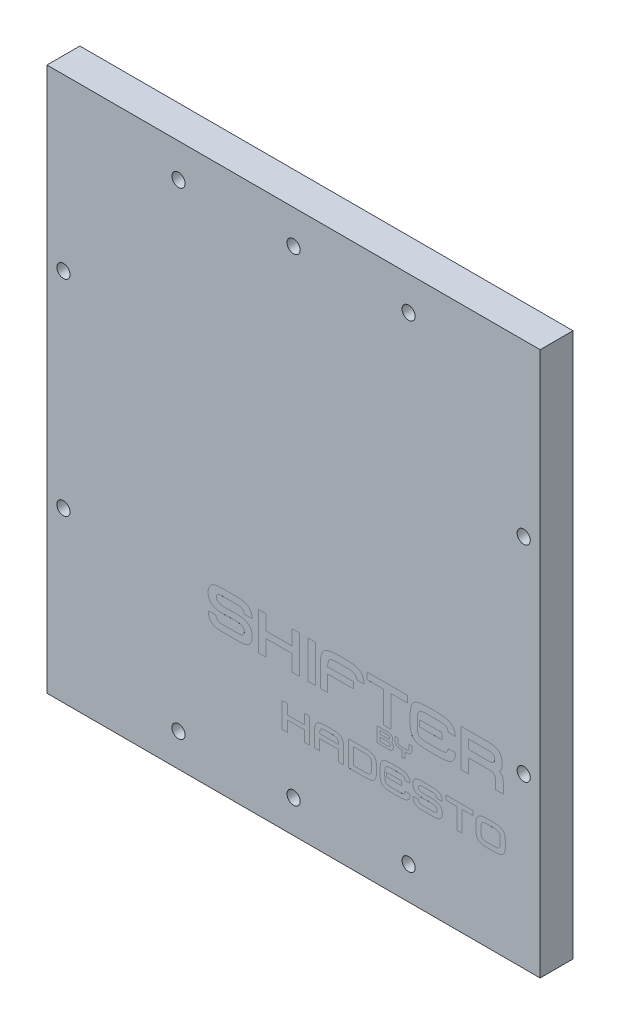
SolidWorks part; units mm, degrees
material "Oak"
ref_plane "Front Plane" through (0, 0, 0) normal (0, 0, 1) x (1, 0, 0)
ref_plane "Top Plane" through (0, 0, 0) normal (0, 1, 0) x (1, 0, 0)
ref_plane "Right Plane" through (0, 0, 0) normal (1, 0, 0) x (0, 0, -1)
sketch "Szkic1" plane through (0, 0, 0) normal (0, 1, 0) x (1, 0, 0)
  line L1 (-75, -5) -> (75, -5)
  line L2 (-75, -5) -> (-75, 5)
  line L3 (-75, 5) -> (75, 5)
  line L4 (75, -5) -> (75, 5)
  line L5 (-75, -5) -> (75, 5) construction
  line L6 (-75, 5) -> (75, -5) construction
  point P0 (0, 0)
extrude "Dodanie-wyciągnięcie1" add sketch "Szkic1" along normal blind 165.5
sketch "Szkic2" plane through (0, 0, 5) normal (0, 0, 1) x (1, 0, 0)
  line L0 (-75, 165.5) -> (-75, 155.25) construction
  line L1 (-75, 165.5) -> (-75, 0) construction
  line L2 (-75, 155.25) -> (-35, 155.25) construction
  line L3 (-35, 155.25) -> (0, 155.25) construction
  line L4 (0, 155.25) -> (35, 155.25) construction
  line L5 (75, 0) -> (75, 10) construction
  line L6 (75, 165.5) -> (75, 0) construction
  line L7 (75, 10) -> (35, 10) construction
  line L8 (35, 10) -> (0, 10) construction
  line L9 (0, 10) -> (-35, 10) construction
  line L10 (-75, 155.25) -> (-75, 145) construction
  line L11 (-75, 145) -> (-70, 145) construction
  line L12 (-70, 145) -> (-70, 113.75) construction
  line L13 (-70, 113.75) -> (-70, 51.25) construction
  line L14 (75, 10) -> (75, 20) construction
  line L15 (75, 20) -> (70, 20) construction
  line L16 (70, 20) -> (70, 51.25) construction
  line L17 (70, 51.25) -> (70, 113.75) construction
  line L18 (-35, 165.5) -> (-35, 155.25) construction
  line L19 (-75, 165.5) -> (75, 165.5) construction
  circle A0 centre (-35, 155.25) radius 2
  circle A1 centre (0, 155.25) radius 2
  circle A2 centre (35, 155.25) radius 2
  circle A3 centre (-35, 10) radius 2
  circle A4 centre (0, 10) radius 2
  circle A5 centre (35, 10) radius 2
  circle A6 centre (-70, 113.75) radius 2
  circle A7 centre (-70, 51.25) radius 2
  circle A8 centre (70, 113.75) radius 2
  circle A9 centre (70, 51.25) radius 2
sketch "Szkic3" plane through (0, 0, 5) normal (0, 0, 1) x (1, 0, 0)
  line L0 (-16.5425, 42.8324) -> (-22.1233, 42.8324)
  line L1 (-25.9282, 46.2952) -> (-23.5548, 46.2952)
  line L2 (-21.7883, 44.8332) -> (-16.9713, 44.8332)
  line L3 (-22.1537, 54.2751) -> (-16.8447, 54.2751)
  line L4 (-12.6205, 50.8264) -> (-15.0712, 50.8264)
  line L5 (-17.0205, 52.2883) -> (-22.0272, 52.2883)
  line L6 (1.875, 42.8324) -> (-0.4656, 42.8324)
  line L7 (-0.4656, 42.8324) -> (-0.4656, 47.7431)
  line L8 (-0.4656, 47.7431) -> (-8.3283, 47.7431)
  line L9 (-8.3283, 47.7431) -> (-8.3283, 42.8324)
  line L10 (-8.3283, 42.8324) -> (-10.6689, 42.8324)
  line L11 (-10.6689, 42.8324) -> (-10.6689, 54.2751)
  line L12 (-10.6689, 54.2751) -> (-8.3283, 54.2751)
  line L13 (-8.3283, 54.2751) -> (-8.3283, 49.7275)
  line L14 (-8.3283, 49.7275) -> (-0.4656, 49.7275)
  line L15 (-0.4656, 49.7275) -> (-0.4656, 54.2751)
  line L16 (-0.4656, 54.2751) -> (1.875, 54.2751)
  line L17 (1.875, 54.2751) -> (1.875, 42.8324)
  line L18 (6.706, 42.8324) -> (4.3655, 42.8324)
  line L19 (4.3655, 42.8324) -> (4.3655, 54.2751)
  line L20 (4.3655, 54.2751) -> (6.706, 54.2751)
  line L21 (6.706, 54.2751) -> (6.706, 42.8324)
  line L22 (10.3539, 49.6807) -> (18.205, 49.6807)
  line L23 (18.205, 49.6807) -> (18.205, 47.7759)
  line L24 (18.205, 47.7759) -> (10.3539, 47.7759)
  line L25 (10.3539, 47.7759) -> (10.3539, 42.8324)
  line L26 (10.3539, 42.8324) -> (8.1235, 42.8324)
  line L27 (8.1235, 42.8324) -> (8.1399, 48.767)
  line L28 (13.7089, 54.3384) -> (15.7754, 54.3384)
  line L29 (21.5108, 50.653) -> (19.2944, 50.653)
  line L30 (15.6957, 52.3047) -> (13.8214, 52.3047)
  line L31 (34.6708, 52.2743) -> (29.6477, 52.2743)
  line L32 (29.6477, 52.2743) -> (29.6477, 42.8324)
  line L33 (29.6477, 42.8324) -> (27.3071, 42.8324)
  line L34 (27.3071, 42.8324) -> (27.3071, 52.2743)
  line L35 (27.3071, 52.2743) -> (22.3003, 52.2743)
  line L36 (22.3003, 52.2743) -> (22.3003, 54.2751)
  line L37 (22.3003, 54.2751) -> (34.6708, 54.2751)
  line L38 (34.6708, 54.2751) -> (34.6708, 52.2743)
  line L39 (43.4309, 42.8324) -> (40.9685, 42.8324)
  line L40 (40.999, 54.322) -> (43.4637, 54.322)
  line L41 (49.1991, 50.7467) -> (46.9523, 50.7467)
  line L42 (43.3841, 52.3211) -> (41.1115, 52.3211)
  line L43 (37.6252, 49.5284) -> (37.6276, 47.9235)
  line L44 (41.0623, 44.8004) -> (43.4005, 44.8004)
  line L45 (46.9687, 46.4217) -> (49.2296, 46.4217)
  line L46 (45.1764, 47.7759) -> (38.3328, 47.7993)
  line L47 (38.3328, 47.7993) -> (38.3328, 49.6971)
  line L48 (38.3328, 49.6971) -> (45.1764, 49.6971)
  line L49 (45.1764, 49.6971) -> (45.1764, 47.7759)
  line L50 (63.7883, 42.8324) -> (61.4642, 42.8324)
  line L51 (61.4642, 42.8324) -> (61.4642, 45.016)
  line L52 (59.4516, 47.1082) -> (53.2664, 47.0918)
  line L53 (53.2664, 47.0918) -> (53.2664, 42.8324)
  line L54 (53.2664, 42.8324) -> (50.9891, 42.8324)
  line L55 (50.9891, 42.8324) -> (50.9891, 54.2751)
  line L56 (50.9891, 54.2751) -> (59.2923, 54.2751)
  line L57 (63.7883, 45.7634) -> (63.7883, 42.8324)
  line L58 (59.468, 52.0681) -> (53.2664, 52.0681)
  line L59 (53.2664, 52.0681) -> (53.2664, 49.2988)
  line L60 (53.2664, 49.2988) -> (59.468, 49.2988)
  line L61 (4.9001, 26.251) -> (3.3398, 26.251)
  line L62 (3.3398, 26.251) -> (3.3398, 29.5248)
  line L63 (3.3398, 29.5248) -> (-1.9021, 29.5248)
  line L64 (-1.9021, 29.5248) -> (-1.9021, 26.251)
  line L65 (-1.9021, 26.251) -> (-3.4624, 26.251)
  line L66 (-3.4624, 26.251) -> (-3.4624, 33.8794)
  line L67 (-3.4624, 33.8794) -> (-1.9021, 33.8794)
  line L68 (-1.9021, 33.8794) -> (-1.9021, 30.8477)
  line L69 (-1.9021, 30.8477) -> (3.3398, 30.8477)
  line L70 (3.3398, 30.8477) -> (3.3398, 33.8794)
  line L71 (3.3398, 33.8794) -> (4.9001, 33.8794)
  line L72 (4.9001, 33.8794) -> (4.9001, 26.251)
  line L73 (7.9396, 30.8477) -> (13.6922, 30.8477)
  line L74 (11.5133, 32.5455) -> (9.9983, 32.5455)
  line L75 (13.7016, 29.5248) -> (7.9412, 29.5248)
  line L76 (7.9412, 29.5248) -> (7.9412, 26.251)
  line L77 (7.9412, 26.251) -> (6.3808, 26.251)
  line L78 (6.3808, 26.251) -> (6.3808, 30.7587)
  line L79 (9.828, 33.8794) -> (11.7039, 33.8794)
  line L80 (15.2635, 30.7587) -> (15.2635, 26.251)
  line L81 (15.2635, 26.251) -> (13.7016, 26.251)
  line L82 (13.7016, 26.251) -> (13.7016, 29.5248)
  line L83 (21.9892, 26.24) -> (16.6552, 26.24)
  line L84 (16.6552, 26.24) -> (16.6552, 33.8794)
  line L85 (16.6552, 33.8794) -> (21.8096, 33.8794)
  line L86 (23.7011, 29.6138) -> (23.7011, 30.5463)
  line L87 (21.7252, 32.5549) -> (18.2265, 32.5549)
  line L88 (18.2265, 32.5549) -> (18.2265, 27.5739)
  line L89 (18.2265, 27.5739) -> (21.8205, 27.5739)
  line L90 (31.6044, 26.251) -> (29.9629, 26.251)
  line L91 (29.9832, 33.9107) -> (31.6263, 33.9107)
  line L92 (35.4499, 31.5272) -> (33.952, 31.5272)
  line L93 (31.5732, 32.5768) -> (30.0581, 32.5768)
  line L94 (27.734, 30.715) -> (27.7355, 29.645)
  line L95 (30.0253, 27.563) -> (31.5841, 27.563)
  line L96 (33.963, 28.6438) -> (35.4702, 28.6438)
  line L97 (32.7681, 29.5466) -> (28.2057, 29.5623)
  line L98 (28.2057, 29.5623) -> (28.2057, 30.8337)
  line L99 (28.2057, 30.8337) -> (32.7681, 30.8274)
  line L100 (32.7681, 30.8274) -> (32.7681, 29.5466)
  line L101 (42.6036, 26.251) -> (38.883, 26.251)
  line L102 (36.3465, 28.5595) -> (37.9287, 28.5595)
  line L103 (39.1064, 27.5848) -> (42.3177, 27.5848)
  line L104 (38.8627, 33.8794) -> (42.4021, 33.8794)
  line L105 (45.2182, 31.5803) -> (43.5845, 31.5803)
  line L106 (42.2849, 32.5549) -> (38.9471, 32.5549)
  line L107 (54.5539, 32.5455) -> (51.2051, 32.5455)
  line L108 (51.2051, 32.5455) -> (51.2051, 26.251)
  line L109 (51.2051, 26.251) -> (49.6447, 26.251)
  line L110 (49.6447, 26.251) -> (49.6447, 32.5455)
  line L111 (49.6447, 32.5455) -> (46.3069, 32.5455)
  line L112 (46.3069, 32.5455) -> (46.3069, 33.8794)
  line L113 (46.3069, 33.8794) -> (54.5539, 33.8794)
  line L114 (54.5539, 33.8794) -> (54.5539, 32.5455)
  line L115 (60.5002, 26.251) -> (59.1335, 26.251)
  line L116 (59.1538, 33.9216) -> (60.5111, 33.9216)
  line L117 (62.8477, 29.6888) -> (62.8477, 30.3979)
  line L118 (60.458, 32.4815) -> (59.2287, 32.4815)
  line L119 (57.0014, 30.3885) -> (57.0014, 29.6778)
  line L120 (59.1975, 27.6692) -> (60.4783, 27.6692)
  spline S0 degree 3 poles (-12.5713, 46.2577) (-12.5722, 45.9664) (-12.5971, 45.5408) (-12.7128, 45.0029) (-12.83, 44.6437) (-12.9796, 44.3159) (-13.2238, 43.9226) (-13.462, 43.6722) (-13.6397, 43.5306) knots 0 0 0 0 0.288468 0.419708 0.543339 0.661573 0.775414 1 1 1 1
  spline S1 degree 3 poles (-13.6397, 43.5306) (-13.7956, 43.405) (-14.0684, 43.2543) (-14.4678, 43.0951) (-14.8161, 43.0021) (-15.1968, 42.9241) (-15.7757, 42.8517) (-16.2289, 42.8331) (-16.5425, 42.8324) knots 0 0 0 0 0.196905 0.306371 0.424122 0.552441 0.690159 1 1 1 1
  spline S2 degree 3 poles (-22.1233, 42.8324) (-22.422, 42.8344) (-22.8582, 42.854) (-23.4142, 42.9477) (-23.7888, 43.04) (-24.1336, 43.1621) (-24.4483, 43.3123) (-24.7349, 43.4871) (-24.9872, 43.6949) (-25.2139, 43.9236) (-25.4089, 44.1827) (-25.5687, 44.4703) (-25.7049, 44.7826) (-25.8063, 45.1234) (-25.9058, 45.628) (-25.9273, 46.0244) (-25.9282, 46.2952) knots 0 0 0 0 0.151922 0.221135 0.286192 0.347689 0.406613 0.463101 0.517821 0.572256 0.62638 0.681995 0.739047 0.799173 0.862284 1 1 1 1
  spline S3 degree 3 poles (-23.5548, 46.2952) (-23.5548, 46.1808) (-23.5432, 46.0128) (-23.4942, 45.8007) (-23.4488, 45.6557) (-23.3843, 45.5245) (-23.3085, 45.4034) (-23.2203, 45.2915) (-23.1122, 45.1968) (-22.9959, 45.1079) (-22.8624, 45.037) (-22.7184, 44.9718) (-22.5586, 44.9215) (-22.3854, 44.8818) (-22.1277, 44.8442) (-21.9269, 44.8304) (-21.7883, 44.8332) knots 0 0 0 0 0.130945 0.191386 0.248712 0.304229 0.357995 0.411968 0.466331 0.521876 0.579035 0.638606 0.702429 0.770232 0.841588 1 1 1 1
  spline S4 degree 3 poles (-16.9713, 44.8332) (-16.8211, 44.8336) (-16.6038, 44.8417) (-16.3246, 44.8653) (-16.1399, 44.8953) (-15.9696, 44.9248) (-15.7743, 44.9853) (-15.6357, 45.0343) (-15.5538, 45.0816) knots 0 0 0 0 0.310015 0.449363 0.57828 0.696618 0.805875 1 1 1 1
  spline S5 degree 3 poles (-15.5538, 45.0816) (-15.4606, 45.1333) (-15.3318, 45.2304) (-15.1981, 45.3974) (-15.1156, 45.5375) (-15.0561, 45.6959) (-14.9882, 45.9333) (-14.9809, 46.1266) (-14.9775, 46.2577) knots 0 0 0 0 0.232178 0.345784 0.463842 0.584405 0.713048 1 1 1 1
  spline S6 degree 3 poles (-14.9775, 46.2577) (-14.9803, 46.4053) (-15.0015, 46.6269) (-15.1181, 46.8905) (-15.2304, 47.0659) (-15.3779, 47.2214) (-15.6263, 47.4094) (-15.8492, 47.5073) (-16.006, 47.5604) knots 0 0 0 0 0.249245 0.364726 0.480164 0.596826 0.721947 1 1 1 1
  spline S7 degree 3 poles (-16.006, 47.5604) (-16.1277, 47.6026) (-16.3234, 47.6529) (-16.6003, 47.7037) (-16.8364, 47.7359) (-17.0927, 47.7614) (-17.4737, 47.7879) (-17.7702, 47.7891) (-17.974, 47.7923) knots 0 0 0 0 0.194055 0.304223 0.424293 0.553298 0.692568 1 1 1 1
  spline S8 degree 3 poles (-17.974, 47.7923) (-18.1958, 47.7915) (-18.5622, 47.7871) (-19.0955, 47.7678) (-19.5742, 47.7525) (-20.053, 47.7372) (-20.5893, 47.7177) (-20.9589, 47.7135) (-21.1838, 47.7127) knots 0 0 0 0 0.207249 0.342309 0.498541 0.654773 0.789832 1 1 1 1
  spline S9 degree 3 poles (-21.1838, 47.7127) (-21.5213, 47.7157) (-22.0113, 47.7254) (-22.6409, 47.7824) (-23.0635, 47.8443) (-23.4542, 47.9175) (-23.9144, 48.0333) (-24.2341, 48.1563) (-24.431, 48.2515) knots 0 0 0 0 0.305274 0.442866 0.571301 0.691383 0.802203 1 1 1 1
  spline S10 degree 3 poles (-24.431, 48.2515) (-24.6786, 48.375) (-25.0201, 48.6072) (-25.3906, 49.003) (-25.6101, 49.3368) (-25.783, 49.7059) (-25.9488, 50.267) (-25.9946, 50.717) (-25.9914, 51.0255) knots 0 0 0 0 0.24616 0.363762 0.480638 0.600407 0.725359 1 1 1 1
  spline S11 degree 3 poles (-25.9914, 51.0255) (-25.9927, 51.3039) (-25.9626, 51.7098) (-25.8472, 52.2226) (-25.7313, 52.5649) (-25.5783, 52.8745) (-25.3286, 53.2434) (-25.0931, 53.4792) (-24.9137, 53.6074) knots 0 0 0 0 0.287332 0.417925 0.54153 0.659382 0.773151 1 1 1 1
  spline S12 degree 3 poles (-24.9137, 53.6074) (-24.7536, 53.7243) (-24.4854, 53.8727) (-24.0922, 54.0226) (-23.7601, 54.1144) (-23.3992, 54.1874) (-22.8619, 54.2559) (-22.4425, 54.2784) (-22.1537, 54.2751) knots 0 0 0 0 0.205829 0.317156 0.436985 0.563785 0.699798 1 1 1 1
  spline S13 degree 3 poles (-16.8447, 54.2751) (-16.514, 54.2729) (-16.032, 54.2538) (-15.4167, 54.1597) (-15.0024, 54.0678) (-14.6215, 53.9455) (-14.2721, 53.7988) (-13.9567, 53.623) (-13.6744, 53.4194) (-13.4246, 53.1899) (-13.2094, 52.9306) (-13.0252, 52.6466) (-12.8778, 52.333) (-12.7598, 51.9949) (-12.6489, 51.4922) (-12.6205, 51.0969) (-12.6205, 50.8264) knots 0 0 0 0 0.159185 0.231381 0.299177 0.363087 0.423506 0.481188 0.536339 0.590564 0.643901 0.697977 0.752917 0.810175 0.869863 1 1 1 1
  spline S14 degree 3 poles (-15.0712, 50.8264) (-15.0691, 50.9412) (-15.0855, 51.1087) (-15.1351, 51.3221) (-15.19, 51.4655) (-15.2574, 51.5988) (-15.3439, 51.7184) (-15.4411, 51.8304) (-15.5589, 51.9255) (-15.6873, 52.0143) (-15.8347, 52.085) (-15.9946, 52.1496) (-16.1706, 52.2) (-16.3616, 52.2402) (-16.646, 52.2769) (-16.8677, 52.2916) (-17.0205, 52.2883) knots 0 0 0 0 0.123736 0.18099 0.235951 0.289117 0.341746 0.394885 0.448749 0.504633 0.563073 0.624754 0.690648 0.760424 0.8353 1 1 1 1
  spline S15 degree 3 poles (-22.0272, 52.2883) (-22.2371, 52.2869) (-22.5405, 52.2592) (-22.8972, 52.1172) (-23.1063, 51.9741) (-23.2671, 51.7854) (-23.4277, 51.4644) (-23.4554, 51.1829) (-23.4587, 50.9927) knots 0 0 0 0 0.286177 0.406449 0.517602 0.626596 0.73942 1 1 1 1
  spline S16 degree 3 poles (-23.4587, 50.9927) (-23.457, 50.8857) (-23.4397, 50.7253) (-23.3611, 50.5294) (-23.2838, 50.394) (-23.1812, 50.2708) (-23.0548, 50.1609) (-22.908, 50.0593) (-22.739, 49.9686) (-22.5482, 49.8892) (-22.3348, 49.8213) (-22.0996, 49.7644) (-21.8419, 49.7141) (-21.5617, 49.6777) (-21.1439, 49.6434) (-20.8193, 49.6322) (-20.5957, 49.6338) knots 0 0 0 0 0.091833 0.135566 0.179508 0.224525 0.271785 0.322124 0.376754 0.435361 0.498446 0.567863 0.641921 0.722688 0.809065 1 1 1 1
  spline S17 degree 3 poles (-20.5957, 49.6338) (-20.3847, 49.6313) (-20.0411, 49.645) (-19.5468, 49.6639) (-19.1135, 49.688) (-18.6816, 49.71) (-18.1961, 49.7357) (-17.86, 49.7408) (-17.6554, 49.7439) knots 0 0 0 0 0.215037 0.3505 0.504367 0.657438 0.791346 1 1 1 1
  spline S18 degree 3 poles (-17.6554, 49.7439) (-17.3013, 49.7442) (-16.7871, 49.7276) (-16.1262, 49.6657) (-15.6825, 49.5961) (-15.2721, 49.5153) (-14.7902, 49.377) (-14.4514, 49.2483) (-14.2465, 49.1371) knots 0 0 0 0 0.304045 0.441512 0.569747 0.689567 0.800388 1 1 1 1
  spline S19 degree 3 poles (-14.2465, 49.1371) (-13.9801, 49.0015) (-13.6163, 48.7484) (-13.2176, 48.3282) (-12.9809, 47.9812) (-12.7966, 47.5998) (-12.617, 47.0288) (-12.5698, 46.5702) (-12.5713, 46.2577) knots 0 0 0 0 0.254404 0.37397 0.491718 0.610756 0.733649 1 1 1 1
  spline S20 degree 3 poles (8.1399, 48.767) (8.1362, 49.1295) (8.1517, 49.6538) (8.1869, 50.3257) (8.2303, 50.7693) (8.2805, 51.1728) (8.3587, 51.6344) (8.4451, 51.9562) (8.5124, 52.1548) knots 0 0 0 0 0.317801 0.45977 0.589762 0.708489 0.816214 1 1 1 1
  spline S21 degree 3 poles (8.5124, 52.1548) (8.5823, 52.3536) (8.7152, 52.6374) (8.9421, 52.982) (9.1387, 53.211) (9.3602, 53.4154) (9.6921, 53.6615) (9.973, 53.8027) (10.1688, 53.8815) knots 0 0 0 0 0.255571 0.378596 0.499596 0.620993 0.743641 1 1 1 1
  spline S22 degree 3 poles (10.1688, 53.8815) (10.3771, 53.968) (10.7195, 54.064) (11.2069, 54.1671) (11.6307, 54.227) (12.0937, 54.2803) (12.7906, 54.3259) (13.3339, 54.3388) (13.7089, 54.3384) knots 0 0 0 0 0.188097 0.296817 0.416308 0.545737 0.686461 1 1 1 1
  spline S23 degree 3 poles (15.7754, 54.3384) (16.2552, 54.3384) (16.9455, 54.3195) (17.8243, 54.2409) (18.3919, 54.1568) (18.9002, 54.0541) (19.464, 53.8884) (19.8483, 53.725) (20.0676, 53.5816) knots 0 0 0 0 0.326658 0.469759 0.60036 0.717142 0.822452 1 1 1 1
  spline S24 degree 3 poles (20.0676, 53.5816) (20.2708, 53.4493) (20.5514, 53.2043) (20.848, 52.7998) (21.047, 52.4533) (21.2078, 52.0614) (21.3982, 51.4654) (21.4729, 50.9844) (21.5108, 50.653) knots 0 0 0 0 0.215512 0.327131 0.444654 0.569708 0.702963 1 1 1 1
  spline S25 degree 3 poles (19.2944, 50.653) (19.2538, 50.8306) (19.1749, 51.0836) (19.0275, 51.3916) (18.8996, 51.5854) (18.756, 51.7535) (18.5427, 51.944) (18.3519, 52.0428) (18.219, 52.0892) knots 0 0 0 0 0.291344 0.422029 0.544637 0.661528 0.774774 1 1 1 1
  spline S26 degree 3 poles (18.219, 52.0892) (18.0932, 52.1354) (17.8772, 52.1774) (17.5622, 52.2242) (17.2667, 52.2535) (16.9315, 52.2767) (16.4035, 52.298) (15.9871, 52.3079) (15.6957, 52.3047) knots 0 0 0 0 0.157647 0.259244 0.376059 0.508256 0.65595 1 1 1 1
  spline S27 degree 3 poles (13.8214, 52.3047) (13.498, 52.3039) (13.0366, 52.294) (12.4539, 52.2529) (12.0876, 52.2099) (11.7694, 52.1513) (11.4332, 52.0702) (11.2106, 51.9812) (11.0896, 51.8994) knots 0 0 0 0 0.347896 0.496132 0.628134 0.744282 0.843901 1 1 1 1
  spline S28 degree 3 poles (11.0896, 51.8994) (10.9672, 51.823) (10.8144, 51.6538) (10.6572, 51.3775) (10.5595, 51.1174) (10.4778, 50.8178) (10.3906, 50.3365) (10.3615, 49.951) (10.3539, 49.6807) knots 0 0 0 0 0.177191 0.278825 0.393353 0.521096 0.66412 1 1 1 1
  spline S29 degree 3 poles (49.2296, 46.4217) (49.2301, 46.0648) (49.1922, 45.5471) (49.0255, 44.9035) (48.8535, 44.4908) (48.6344, 44.1265) (48.2729, 43.7059) (47.9248, 43.4733) (47.6762, 43.3549) knots 0 0 0 0 0.294114 0.424501 0.54583 0.660956 0.773103 1 1 1 1
  spline S30 degree 3 poles (47.6762, 43.3549) (47.4649, 43.2548) (47.1022, 43.1355) (46.5648, 43.0284) (46.0664, 42.9576) (45.5023, 42.8987) (44.6164, 42.847) (43.9185, 42.829) (43.4309, 42.8324) knots 0 0 0 0 0.16271 0.264982 0.381608 0.513497 0.660216 1 1 1 1
  spline S31 degree 3 poles (40.9685, 42.8324) (40.6006, 42.8331) (40.0683, 42.8441) (39.3856, 42.8848) (38.933, 42.9282) (38.5214, 42.9874) (38.0474, 43.0717) (37.7161, 43.1615) (37.5128, 43.2377) knots 0 0 0 0 0.315853 0.456902 0.58691 0.70608 0.813768 1 1 1 1
  spline S32 degree 3 poles (37.5128, 43.2377) (37.3157, 43.308) (37.0371, 43.4466) (36.699, 43.6791) (36.4767, 43.8806) (36.2743, 44.102) (36.0373, 44.4384) (35.8937, 44.7167) (35.8212, 44.9152) knots 0 0 0 0 0.254655 0.377777 0.499186 0.619886 0.74278 1 1 1 1
  spline S33 degree 3 poles (35.8212, 44.9152) (35.744, 45.1184) (35.6573, 45.4504) (35.5668, 45.9233) (35.5137, 46.3359) (35.4646, 46.7879) (35.4262, 47.4708) (35.4136, 48.003) (35.4135, 48.371) knots 0 0 0 0 0.186213 0.294014 0.413081 0.543143 0.684177 1 1 1 1
  spline S34 degree 3 poles (35.4135, 48.371) (35.4129, 48.7639) (35.4211, 49.3305) (35.4592, 50.0561) (35.499, 50.5326) (35.5472, 50.9657) (35.6223, 51.4555) (35.7024, 51.7975) (35.7673, 52.0072) knots 0 0 0 0 0.321609 0.463729 0.594587 0.712971 0.820379 1 1 1 1
  spline S35 degree 3 poles (35.7673, 52.0072) (35.8342, 52.2208) (35.9606, 52.5271) (36.1869, 52.896) (36.3792, 53.14) (36.5946, 53.3595) (36.9232, 53.6156) (37.2, 53.7665) (37.3956, 53.8464) knots 0 0 0 0 0.264263 0.388826 0.509594 0.630161 0.750928 1 1 1 1
  spline S36 degree 3 poles (37.3956, 53.8464) (37.6048, 53.9369) (37.9501, 54.0386) (38.4431, 54.1434) (38.8728, 54.2071) (39.3449, 54.2584) (40.0578, 54.3088) (40.6146, 54.3235) (40.999, 54.322) knots 0 0 0 0 0.186673 0.294794 0.413465 0.543078 0.684474 1 1 1 1
  spline S37 degree 3 poles (43.4637, 54.322) (43.9389, 54.3202) (44.6259, 54.3006) (45.5021, 54.2086) (46.0786, 54.1123) (46.6018, 53.9935) (47.2015, 53.8016) (47.6117, 53.611) (47.852, 53.4527) knots 0 0 0 0 0.314845 0.454824 0.583342 0.70181 0.80996 1 1 1 1
  spline S38 degree 3 poles (47.852, 53.4527) (48.0678, 53.3135) (48.367, 53.07) (48.6792, 52.6693) (48.8709, 52.3436) (49.0189, 51.9863) (49.1627, 51.4559) (49.1995, 51.0341) (49.1991, 50.7467) knots 0 0 0 0 0.24395 0.361591 0.480106 0.601286 0.727242 1 1 1 1
  spline S39 degree 3 poles (46.9523, 50.7467) (46.9502, 50.9142) (46.9332, 51.1604) (46.8293, 51.4572) (46.7328, 51.6487) (46.5996, 51.8104) (46.383, 51.9988) (46.1819, 52.0917) (46.0409, 52.136) knots 0 0 0 0 0.281221 0.405304 0.523085 0.637091 0.752607 1 1 1 1
  spline S40 degree 3 poles (46.0409, 52.136) (45.9091, 52.1746) (45.6855, 52.2155) (45.3572, 52.2511) (45.047, 52.2765) (44.6932, 52.2978) (44.1339, 52.3156) (43.6926, 52.3229) (43.3841, 52.3211) knots 0 0 0 0 0.154176 0.25489 0.371156 0.503933 0.653245 1 1 1 1
  spline S41 degree 3 poles (41.1115, 52.3211) (40.7849, 52.3205) (40.3181, 52.3101) (39.7283, 52.2695) (39.3559, 52.226) (39.0321, 52.168) (38.6878, 52.0857) (38.4589, 51.9975) (38.3328, 51.9158) knots 0 0 0 0 0.345644 0.493985 0.62552 0.742253 0.841884 1 1 1 1
  spline S42 degree 3 poles (38.3328, 51.9158) (38.2091, 51.8334) (38.0486, 51.6568) (37.8984, 51.3593) (37.8023, 51.0805) (37.7223, 50.7577) (37.6468, 50.2363) (37.6274, 49.8202) (37.6252, 49.5284) knots 0 0 0 0 0.172183 0.272745 0.386756 0.515244 0.659814 1 1 1 1
  spline S43 degree 3 poles (37.6276, 47.9235) (37.6269, 47.5931) (37.6356, 47.1215) (37.707, 46.5311) (37.7779, 46.1664) (37.8697, 45.8533) (38.015, 45.5259) (38.1684, 45.3238) (38.2953, 45.2315) knots 0 0 0 0 0.347585 0.494831 0.624602 0.737837 0.837036 1 1 1 1
  spline S44 degree 3 poles (38.2953, 45.2315) (38.4155, 45.1459) (38.6399, 45.0528) (38.9783, 44.962) (39.3011, 44.9024) (39.672, 44.8566) (40.2641, 44.8127) (40.7333, 44.7996) (41.0623, 44.8004) knots 0 0 0 0 0.155206 0.255592 0.370997 0.502802 0.651395 1 1 1 1
  spline S45 degree 3 poles (43.4005, 44.8004) (43.716, 44.7987) (44.1659, 44.8059) (44.7346, 44.8237) (45.0915, 44.8451) (45.4025, 44.8702) (45.727, 44.9057) (45.946, 44.9463) (46.0737, 44.9855) knots 0 0 0 0 0.352452 0.50258 0.635404 0.751817 0.851039 1 1 1 1
  spline S46 degree 3 poles (46.0737, 44.9855) (46.2148, 45.0281) (46.4171, 45.119) (46.6311, 45.3116) (46.761, 45.4792) (46.8591, 45.6759) (46.9534, 45.9896) (46.9724, 46.2452) (46.9687, 46.4217) knots 0 0 0 0 0.241561 0.354455 0.467197 0.585823 0.711271 1 1 1 1
  spline S47 degree 3 poles (61.4642, 45.016) (61.4636, 45.1911) (61.4535, 45.4451) (61.4041, 45.767) (61.3594, 45.9795) (61.2953, 46.1707) (61.2184, 46.3419) (61.1291, 46.4951) (61.0227, 46.6278) (60.8978, 46.7429) (60.753, 46.8415) (60.588, 46.9262) (60.4013, 46.9937) (60.193, 47.0445) (59.8754, 47.0951) (59.6247, 47.1097) (59.4516, 47.1082) knots 0 0 0 0 0.155012 0.224176 0.287859 0.346836 0.402173 0.453586 0.503209 0.552091 0.603248 0.657619 0.715748 0.778405 0.846994 1 1 1 1
  spline S48 degree 3 poles (59.2923, 54.2751) (59.6295, 54.2778) (60.117, 54.2535) (60.7382, 54.1669) (61.1482, 54.0808) (61.5184, 53.9622) (61.9492, 53.7828) (62.2348, 53.5983) (62.399, 53.4551) knots 0 0 0 0 0.308563 0.445716 0.573699 0.691456 0.800969 1 1 1 1
  spline S49 degree 3 poles (62.399, 53.4551) (62.5743, 53.2988) (62.8032, 53.0231) (63.0434, 52.604) (63.1876, 52.2503) (63.3035, 51.8647) (63.409, 51.2847) (63.4408, 50.8299) (63.4392, 50.5171) knots 0 0 0 0 0.218919 0.332324 0.450085 0.574982 0.707932 1 1 1 1
  spline S50 degree 3 poles (63.4392, 50.5171) (63.4365, 50.2364) (63.4175, 49.8326) (63.3056, 49.3339) (63.1981, 49.0219) (63.0517, 48.7575) (62.8215, 48.464) (62.5884, 48.3126) (62.4224, 48.2468) knots 0 0 0 0 0.319412 0.455762 0.579144 0.692631 0.7973 1 1 1 1
  spline S51 degree 3 poles (62.4224, 48.2468) (62.5319, 48.2204) (62.6935, 48.1711) (62.8867, 48.0636) (63.0224, 47.9758) (63.1442, 47.8684) (63.257, 47.7483) (63.361, 47.6153) (63.4494, 47.4653) (63.5298, 47.3026) (63.5994, 47.1255) (63.658, 46.9334) (63.7072, 46.7277) (63.7444, 46.507) (63.7785, 46.1844) (63.7898, 45.9346) (63.7883, 45.7634) knots 0 0 0 0 0.109953 0.162653 0.214708 0.266963 0.320181 0.374897 0.430803 0.489254 0.55134 0.615754 0.684501 0.756956 0.833401 1 1 1 1
  spline S52 degree 3 poles (59.468, 49.2988) (59.7135, 49.3026) (60.0682, 49.328) (60.4874, 49.4866) (60.7302, 49.648) (60.9207, 49.8565) (61.1052, 50.2141) (61.1471, 50.5265) (61.1455, 50.7397) knots 0 0 0 0 0.292647 0.414933 0.527702 0.635233 0.746266 1 1 1 1
  spline S53 degree 3 poles (61.1455, 50.7397) (61.1478, 50.9369) (61.1035, 51.2275) (60.9195, 51.5564) (60.7283, 51.748) (60.4847, 51.8935) (60.067, 52.0435) (59.7129, 52.0643) (59.468, 52.0681) knots 0 0 0 0 0.243091 0.351382 0.457894 0.571596 0.697254 1 1 1 1
  spline S54 degree 3 poles (13.6922, 30.8477) (13.6926, 31.0165) (13.6755, 31.2579) (13.6252, 31.5621) (13.573, 31.7545) (13.5056, 31.9225) (13.4018, 32.1088) (13.2935, 32.2205) (13.2127, 32.2769) knots 0 0 0 0 0.324044 0.46416 0.591814 0.70624 0.811083 1 1 1 1
  spline S55 degree 3 poles (13.2127, 32.2769) (13.1367, 32.3293) (12.9975, 32.3881) (12.7881, 32.4454) (12.5894, 32.4818) (12.3621, 32.5111) (12.0001, 32.5382) (11.7139, 32.5451) (11.5133, 32.5455) knots 0 0 0 0 0.158283 0.258942 0.374128 0.506345 0.654083 1 1 1 1
  spline S56 degree 3 poles (9.9983, 32.5455) (9.8087, 32.5445) (9.5374, 32.5393) (9.1947, 32.5097) (8.9784, 32.4784) (8.7884, 32.4408) (8.5851, 32.3806) (8.449, 32.3208) (8.3754, 32.266) knots 0 0 0 0 0.341247 0.488 0.61865 0.734417 0.836097 1 1 1 1
  spline S57 degree 3 poles (8.3754, 32.266) (8.3013, 32.2111) (8.201, 32.1026) (8.1095, 31.92) (8.0483, 31.754) (8.0009, 31.5633) (7.9537, 31.2593) (7.9419, 31.0172) (7.9396, 30.8477) knots 0 0 0 0 0.180375 0.283893 0.398091 0.526429 0.667896 1 1 1 1
  spline S58 degree 3 poles (6.3808, 30.7587) (6.3809, 30.9097) (6.3863, 31.1319) (6.4077, 31.4212) (6.4287, 31.6246) (6.4591, 31.8177) (6.493, 32.0012) (6.533, 32.1752) (6.5823, 32.3388) (6.6344, 32.4936) (6.6942, 32.6388) (6.7612, 32.7736) (6.8329, 32.9002) (6.9129, 33.0158) (7.0264, 33.1556) (7.1201, 33.251) (7.1899, 33.3046) knots 0 0 0 0 0.164418 0.241696 0.315791 0.38688 0.454344 0.518949 0.58099 0.640308 0.696716 0.751711 0.804006 0.854935 0.904496 1 1 1 1
  spline S59 degree 3 poles (7.1899, 33.3046) (7.3198, 33.4093) (7.5515, 33.5388) (7.9014, 33.6616) (8.2133, 33.7425) (8.5634, 33.8034) (9.1045, 33.8661) (9.5316, 33.878) (9.828, 33.8794) knots 0 0 0 0 0.181811 0.287673 0.404741 0.533691 0.675806 1 1 1 1
  spline S60 degree 3 poles (11.7039, 33.8794) (12.0049, 33.8773) (12.439, 33.8673) (12.9894, 33.8019) (13.3459, 33.7388) (13.6651, 33.6597) (14.021, 33.5305) (14.2588, 33.4009) (14.392, 33.2937) knots 0 0 0 0 0.323218 0.46499 0.594403 0.711468 0.817329 1 1 1 1
  spline S61 degree 3 poles (14.392, 33.2937) (14.5412, 33.1757) (14.7359, 32.955) (14.9315, 32.6065) (15.0556, 32.3051) (15.1494, 31.9678) (15.241, 31.4506) (15.263, 31.0415) (15.2635, 30.7587) knots 0 0 0 0 0.20546 0.315073 0.43164 0.557677 0.693518 1 1 1 1
  spline S62 degree 3 poles (25.263, 29.5716) (25.2649, 29.2833) (25.2462, 28.8676) (25.1784, 28.3398) (25.1095, 27.9961) (25.0178, 27.6892) (24.876, 27.3406) (24.7327, 27.1099) (24.6164, 26.9819) knots 0 0 0 0 0.317702 0.457736 0.585992 0.703413 0.810158 1 1 1 1
  spline S63 degree 3 poles (24.6164, 26.9819) (24.5602, 26.9171) (24.4616, 26.831) (24.3173, 26.7284) (24.1989, 26.654) (24.0682, 26.5895) (23.9286, 26.5282) (23.7798, 26.472) (23.6198, 26.4239) (23.4506, 26.38) (23.2705, 26.3434) (23.0817, 26.3096) (22.8824, 26.2857) (22.6736, 26.2656) (22.3749, 26.2431) (22.1454, 26.2418) (21.9892, 26.24) knots 0 0 0 0 0.091644 0.139592 0.1894 0.241249 0.29541 0.352558 0.411446 0.474174 0.539655 0.608107 0.679455 0.754496 0.832729 1 1 1 1
  spline S64 degree 3 poles (21.8096, 33.8794) (22.0644, 33.8791) (22.4339, 33.8671) (22.9057, 33.8129) (23.2192, 33.7617) (23.504, 33.6909) (23.8358, 33.5842) (24.0617, 33.4724) (24.1962, 33.3843) knots 0 0 0 0 0.30972 0.448551 0.576905 0.695522 0.804763 1 1 1 1
  spline S65 degree 3 poles (24.1962, 33.3843) (24.3173, 33.3059) (24.4859, 33.1698) (24.678, 32.9551) (24.8031, 32.7776) (24.9108, 32.584) (25.0378, 32.3002) (25.0974, 32.0693) (25.1287, 31.9114) knots 0 0 0 0 0.241211 0.360252 0.480825 0.603645 0.730356 1 1 1 1
  spline S66 degree 3 poles (25.1287, 31.9114) (25.1533, 31.78) (25.1864, 31.5659) (25.2106, 31.2581) (25.2328, 30.9813) (25.2449, 30.6734) (25.2612, 30.2002) (25.2631, 29.8293) (25.263, 29.5716) knots 0 0 0 0 0.170985 0.276567 0.394702 0.525969 0.670487 1 1 1 1
  spline S67 degree 3 poles (23.7011, 30.5463) (23.7019, 30.7299) (23.6898, 30.9931) (23.6509, 31.3266) (23.6068, 31.5395) (23.553, 31.7286) (23.4871, 31.8936) (23.4067, 32.0335) (23.3127, 32.1521) (23.1972, 32.2494) (23.0608, 32.3336) (22.898, 32.4) (22.7125, 32.4591) (22.5006, 32.5003) (22.1701, 32.5472) (21.9075, 32.5537) (21.7252, 32.5549) knots 0 0 0 0 0.163968 0.235228 0.299821 0.35797 0.410753 0.458068 0.501732 0.545277 0.592271 0.644375 0.701903 0.766041 0.836961 1 1 1 1
  spline S68 degree 3 poles (21.8205, 27.5739) (22.0065, 27.5747) (22.2735, 27.5823) (22.6092, 27.6274) (22.8207, 27.6724) (23.0054, 27.727) (23.205, 27.8161) (23.3299, 27.9099) (23.3949, 27.9831) knots 0 0 0 0 0.33456 0.479099 0.608331 0.7229 0.824679 1 1 1 1
  spline S69 degree 3 poles (23.3949, 27.9831) (23.4525, 28.0548) (23.5234, 28.1872) (23.5846, 28.3917) (23.6294, 28.5818) (23.6596, 28.8005) (23.6962, 29.1468) (23.6997, 29.4217) (23.7011, 29.6138) knots 0 0 0 0 0.163305 0.264522 0.379735 0.511061 0.657458 1 1 1 1
  spline S70 degree 3 poles (35.4702, 28.6438) (35.4706, 28.4059) (35.4453, 28.0608) (35.3342, 27.6317) (35.2195, 27.3566) (35.0734, 27.1137) (34.8324, 26.8333) (34.6004, 26.6782) (34.4347, 26.5993) knots 0 0 0 0 0.294114 0.424501 0.54583 0.660956 0.773103 1 1 1 1
  spline S71 degree 3 poles (34.4347, 26.5993) (34.2938, 26.5325) (34.052, 26.4531) (33.6937, 26.3817) (33.3615, 26.3344) (32.9854, 26.2952) (32.3948, 26.2607) (31.9295, 26.2487) (31.6044, 26.251) knots 0 0 0 0 0.16271 0.264982 0.381608 0.513497 0.660216 1 1 1 1
  spline S72 degree 3 poles (29.9629, 26.251) (29.7176, 26.2514) (29.3627, 26.2587) (28.9076, 26.2859) (28.6058, 26.3149) (28.3314, 26.3543) (28.0154, 26.4105) (27.7946, 26.4704) (27.659, 26.5212) knots 0 0 0 0 0.315853 0.456902 0.58691 0.70608 0.813768 1 1 1 1
  spline S73 degree 3 poles (27.659, 26.5212) (27.5277, 26.568) (27.3419, 26.6605) (27.1165, 26.8154) (26.9683, 26.9498) (26.8334, 27.0974) (26.6754, 27.3216) (26.5797, 27.5072) (26.5313, 27.6395) knots 0 0 0 0 0.254655 0.377777 0.499186 0.619886 0.74278 1 1 1 1
  spline S74 degree 3 poles (26.5313, 27.6395) (26.4799, 27.775) (26.4221, 27.9963) (26.3617, 28.3116) (26.3263, 28.5866) (26.2936, 28.8879) (26.268, 29.3433) (26.2596, 29.698) (26.2595, 29.9434) knots 0 0 0 0 0.186213 0.294014 0.413081 0.543143 0.684177 1 1 1 1
  spline S75 degree 3 poles (26.2595, 29.9434) (26.2591, 30.2053) (26.2645, 30.5831) (26.29, 31.0667) (26.3165, 31.3844) (26.3486, 31.6732) (26.3987, 31.9997) (26.4521, 32.2277) (26.4954, 32.3675) knots 0 0 0 0 0.321609 0.463729 0.594587 0.712971 0.820379 1 1 1 1
  spline S76 degree 3 poles (26.4954, 32.3675) (26.54, 32.5099) (26.6242, 32.7141) (26.7751, 32.96) (26.9033, 33.1227) (27.0469, 33.269) (27.266, 33.4398) (27.4505, 33.5404) (27.5809, 33.5936) knots 0 0 0 0 0.264263 0.388826 0.509594 0.630161 0.750928 1 1 1 1
  spline S77 degree 3 poles (27.5809, 33.5936) (27.7204, 33.6539) (27.9506, 33.7218) (28.2792, 33.7916) (28.5657, 33.8341) (28.8804, 33.8683) (29.3557, 33.9019) (29.7269, 33.9117) (29.9832, 33.9107) knots 0 0 0 0 0.186673 0.294794 0.413465 0.543078 0.684474 1 1 1 1
  spline S78 degree 3 poles (31.6263, 33.9107) (31.9431, 33.9095) (32.4011, 33.8964) (32.9853, 33.8351) (33.3695, 33.7709) (33.7184, 33.6917) (34.1182, 33.5637) (34.3916, 33.4367) (34.5518, 33.3312) knots 0 0 0 0 0.314845 0.454824 0.583342 0.70181 0.80996 1 1 1 1
  spline S79 degree 3 poles (34.5518, 33.3312) (34.6957, 33.2383) (34.8952, 33.076) (35.1033, 32.8089) (35.2311, 32.5918) (35.3298, 32.3536) (35.4257, 32) (35.4501, 31.7188) (35.4499, 31.5272) knots 0 0 0 0 0.24395 0.361591 0.480106 0.601286 0.727242 1 1 1 1
  spline S80 degree 3 poles (33.952, 31.5272) (33.9506, 31.6388) (33.9393, 31.803) (33.87, 32.0009) (33.8057, 32.1285) (33.7169, 32.2363) (33.5725, 32.3619) (33.4384, 32.4238) (33.3444, 32.4534) knots 0 0 0 0 0.281221 0.405304 0.523085 0.637091 0.752607 1 1 1 1
  spline S81 degree 3 poles (33.3444, 32.4534) (33.2565, 32.4791) (33.1075, 32.5063) (32.8886, 32.5301) (32.6818, 32.547) (32.446, 32.5612) (32.0731, 32.5731) (31.7789, 32.578) (31.5732, 32.5768) knots 0 0 0 0 0.154176 0.25489 0.371156 0.503933 0.653245 1 1 1 1
  spline S82 degree 3 poles (30.0581, 32.5768) (29.8404, 32.5763) (29.5292, 32.5694) (29.136, 32.5424) (28.8878, 32.5133) (28.6719, 32.4747) (28.4424, 32.4199) (28.2898, 32.361) (28.2057, 32.3066) knots 0 0 0 0 0.345644 0.493985 0.62552 0.742253 0.841884 1 1 1 1
  spline S83 degree 3 poles (28.2057, 32.3066) (28.1232, 32.2517) (28.0162, 32.1339) (27.9161, 31.9355) (27.8521, 31.7497) (27.7987, 31.5345) (27.7483, 31.1869) (27.7354, 30.9095) (27.734, 30.715) knots 0 0 0 0 0.172183 0.272745 0.386756 0.515244 0.659814 1 1 1 1
  spline S84 degree 3 poles (27.7355, 29.645) (27.7351, 29.4248) (27.7409, 29.1103) (27.7885, 28.7168) (27.8358, 28.4736) (27.8969, 28.2649) (27.9938, 28.0466) (28.0961, 27.9119) (28.1807, 27.8504) knots 0 0 0 0 0.347585 0.494831 0.624602 0.737837 0.837036 1 1 1 1
  spline S85 degree 3 poles (28.1807, 27.8504) (28.2608, 27.7933) (28.4104, 27.7312) (28.636, 27.6707) (28.8513, 27.6309) (29.0985, 27.6004) (29.4932, 27.5711) (29.806, 27.5624) (30.0253, 27.563) knots 0 0 0 0 0.155206 0.255592 0.370997 0.502802 0.651395 1 1 1 1
  spline S86 degree 3 poles (31.5841, 27.563) (31.7945, 27.5618) (32.0945, 27.5666) (32.4735, 27.5785) (32.7115, 27.5928) (32.9188, 27.6095) (33.1352, 27.6332) (33.2812, 27.6602) (33.3663, 27.6864) knots 0 0 0 0 0.352452 0.50258 0.635404 0.751817 0.851039 1 1 1 1
  spline S87 degree 3 poles (33.3663, 27.6864) (33.4603, 27.7148) (33.5952, 27.7754) (33.7379, 27.9038) (33.8245, 28.0155) (33.8899, 28.1467) (33.9527, 28.3558) (33.9654, 28.5262) (33.963, 28.6438) knots 0 0 0 0 0.241561 0.354455 0.467197 0.585823 0.711271 1 1 1 1
  spline S88 degree 3 poles (45.251, 28.5345) (45.2504, 28.3403) (45.2338, 28.0566) (45.1567, 27.698) (45.0786, 27.4585) (44.9788, 27.2399) (44.816, 26.9777) (44.6572, 26.8108) (44.5388, 26.7164) knots 0 0 0 0 0.288468 0.419708 0.543339 0.661573 0.775414 1 1 1 1
  spline S89 degree 3 poles (44.5388, 26.7164) (44.4348, 26.6327) (44.253, 26.5322) (43.9867, 26.4261) (43.7545, 26.3641) (43.5007, 26.3121) (43.1148, 26.2638) (42.8126, 26.2514) (42.6036, 26.251) knots 0 0 0 0 0.196905 0.306371 0.424122 0.552441 0.690159 1 1 1 1
  spline S90 degree 3 poles (38.883, 26.251) (38.6839, 26.2523) (38.3931, 26.2654) (38.0224, 26.3278) (37.7727, 26.3894) (37.5429, 26.4708) (37.333, 26.5709) (37.1419, 26.6874) (36.9738, 26.826) (36.8226, 26.9784) (36.6926, 27.1512) (36.5861, 27.3429) (36.4953, 27.5511) (36.4277, 27.7783) (36.3613, 28.1147) (36.347, 28.379) (36.3465, 28.5595) knots 0 0 0 0 0.151922 0.221135 0.286192 0.347689 0.406613 0.463101 0.517821 0.572256 0.62638 0.681995 0.739047 0.799173 0.862284 1 1 1 1
  spline S91 degree 3 poles (37.9287, 28.5595) (37.9287, 28.4832) (37.9364, 28.3712) (37.9691, 28.2298) (37.9994, 28.1331) (38.0424, 28.0457) (38.0929, 27.9649) (38.1517, 27.8904) (38.2238, 27.8272) (38.3013, 27.7679) (38.3903, 27.7207) (38.4863, 27.6772) (38.5928, 27.6437) (38.7083, 27.6172) (38.8801, 27.5922) (39.0139, 27.5829) (39.1064, 27.5848) knots 0 0 0 0 0.130945 0.191386 0.248712 0.304229 0.357995 0.411968 0.466331 0.521876 0.579035 0.638606 0.702429 0.770232 0.841588 1 1 1 1
  spline S92 degree 3 poles (42.3177, 27.5848) (42.4178, 27.5851) (42.5627, 27.5905) (42.7488, 27.6062) (42.872, 27.6263) (42.9855, 27.6459) (43.1157, 27.6862) (43.2081, 27.7189) (43.2627, 27.7504) knots 0 0 0 0 0.310015 0.449363 0.57828 0.696618 0.805875 1 1 1 1
  spline S93 degree 3 poles (43.2627, 27.7504) (43.3248, 27.7849) (43.4107, 27.8496) (43.4998, 27.9609) (43.5549, 28.0544) (43.5945, 28.1599) (43.6398, 28.3182) (43.6446, 28.4471) (43.6469, 28.5345) knots 0 0 0 0 0.232178 0.345784 0.463842 0.584405 0.713048 1 1 1 1
  spline S94 degree 3 poles (43.6469, 28.5345) (43.6451, 28.6329) (43.6309, 28.7806) (43.5532, 28.9563) (43.4783, 29.0733) (43.3799, 29.177) (43.2144, 29.3023) (43.0658, 29.3675) (42.9612, 29.4029) knots 0 0 0 0 0.249245 0.364726 0.480164 0.596826 0.721947 1 1 1 1
  spline S95 degree 3 poles (42.9612, 29.4029) (42.8801, 29.4311) (42.7496, 29.4646) (42.5651, 29.4985) (42.4076, 29.52) (42.2367, 29.537) (41.9827, 29.5546) (41.7851, 29.5554) (41.6492, 29.5576) knots 0 0 0 0 0.194055 0.304223 0.424293 0.553298 0.692568 1 1 1 1
  spline S96 degree 3 poles (41.6492, 29.5576) (41.5013, 29.557) (41.2571, 29.5541) (40.9016, 29.5412) (40.5824, 29.531) (40.2633, 29.5208) (39.9057, 29.5078) (39.6593, 29.505) (39.5094, 29.5045) knots 0 0 0 0 0.207249 0.342309 0.498541 0.654773 0.789832 1 1 1 1
  spline S97 degree 3 poles (39.5094, 29.5045) (39.2844, 29.5065) (38.9577, 29.513) (38.538, 29.551) (38.2562, 29.5923) (37.9958, 29.641) (37.689, 29.7182) (37.4759, 29.8002) (37.3445, 29.8637) knots 0 0 0 0 0.305274 0.442866 0.571301 0.691383 0.802203 1 1 1 1
  spline S98 degree 3 poles (37.3445, 29.8637) (37.1795, 29.946) (36.9518, 30.1008) (36.7048, 30.3647) (36.5585, 30.5872) (36.4433, 30.8333) (36.3327, 31.2074) (36.3022, 31.5073) (36.3043, 31.713) knots 0 0 0 0 0.24616 0.363762 0.480638 0.600407 0.725359 1 1 1 1
  spline S99 degree 3 poles (36.3043, 31.713) (36.3035, 31.8986) (36.3235, 32.1692) (36.4004, 32.5111) (36.4777, 32.7393) (36.5797, 32.9457) (36.7462, 33.1917) (36.9032, 33.3488) (37.0228, 33.4343) knots 0 0 0 0 0.287332 0.417925 0.54153 0.659382 0.773151 1 1 1 1
  spline S100 degree 3 poles (37.0228, 33.4343) (37.1295, 33.5122) (37.3083, 33.6112) (37.5704, 33.7111) (37.7918, 33.7723) (38.0324, 33.8209) (38.3906, 33.8666) (38.6702, 33.8816) (38.8627, 33.8794) knots 0 0 0 0 0.205829 0.317156 0.436985 0.563785 0.699798 1 1 1 1
  spline S101 degree 3 poles (42.4021, 33.8794) (42.6225, 33.878) (42.9439, 33.8652) (43.3541, 33.8025) (43.6303, 33.7412) (43.8842, 33.6597) (44.1172, 33.5619) (44.3274, 33.4447) (44.5156, 33.3089) (44.6822, 33.1559) (44.8256, 32.9831) (44.9484, 32.7938) (45.0467, 32.5847) (45.1254, 32.3593) (45.1993, 32.0242) (45.2182, 31.7606) (45.2182, 31.5803) knots 0 0 0 0 0.159185 0.231381 0.299177 0.363087 0.423506 0.481188 0.536339 0.590564 0.643901 0.697977 0.752917 0.810175 0.869863 1 1 1 1
  spline S102 degree 3 poles (43.5845, 31.5803) (43.5858, 31.6568) (43.5749, 31.7685) (43.5418, 31.9107) (43.5053, 32.0063) (43.4603, 32.0952) (43.4027, 32.1749) (43.3378, 32.2496) (43.2593, 32.313) (43.1737, 32.3723) (43.0754, 32.4193) (42.9688, 32.4624) (42.8515, 32.496) (42.7241, 32.5228) (42.5345, 32.5473) (42.3868, 32.5571) (42.2849, 32.5549) knots 0 0 0 0 0.123736 0.18099 0.235951 0.289117 0.341746 0.394885 0.448749 0.504633 0.563073 0.624754 0.690648 0.760424 0.8353 1 1 1 1
  spline S103 degree 3 poles (38.9471, 32.5549) (38.8072, 32.5539) (38.6049, 32.5355) (38.3671, 32.4408) (38.2277, 32.3455) (38.1205, 32.2196) (38.0134, 32.0056) (37.995, 31.818) (37.9927, 31.6912) knots 0 0 0 0 0.286177 0.406449 0.517602 0.626596 0.73942 1 1 1 1
  spline S104 degree 3 poles (37.9927, 31.6912) (37.9939, 31.6198) (38.0055, 31.5129) (38.0579, 31.3823) (38.1094, 31.292) (38.1778, 31.2099) (38.262, 31.1366) (38.3599, 31.0689) (38.4726, 31.0084) (38.5998, 30.9555) (38.7421, 30.9102) (38.8988, 30.8723) (39.0706, 30.8387) (39.2574, 30.8145) (39.536, 30.7916) (39.7524, 30.7842) (39.9014, 30.7852) knots 0 0 0 0 0.091833 0.135566 0.179508 0.224525 0.271785 0.322124 0.376754 0.435361 0.498446 0.567863 0.641921 0.722688 0.809065 1 1 1 1
  spline S105 degree 3 poles (39.9014, 30.7852) (40.0421, 30.7836) (40.2711, 30.7927) (40.6007, 30.8053) (40.8896, 30.8214) (41.1775, 30.8361) (41.5012, 30.8531) (41.7252, 30.8566) (41.8616, 30.8587) knots 0 0 0 0 0.215037 0.3505 0.504367 0.657438 0.791346 1 1 1 1
  spline S106 degree 3 poles (41.8616, 30.8587) (42.0977, 30.8589) (42.4405, 30.8477) (42.8811, 30.8065) (43.1769, 30.7601) (43.4505, 30.7062) (43.7718, 30.614) (43.9976, 30.5282) (44.1342, 30.4541) knots 0 0 0 0 0.304045 0.441512 0.569747 0.689567 0.800388 1 1 1 1
  spline S107 degree 3 poles (44.1342, 30.4541) (44.3119, 30.3637) (44.5544, 30.195) (44.8202, 29.9148) (44.9779, 29.6835) (45.1008, 29.4292) (45.2205, 29.0486) (45.2521, 28.7428) (45.251, 28.5345) knots 0 0 0 0 0.254404 0.37397 0.491718 0.610756 0.733649 1 1 1 1
  spline S108 degree 3 poles (64.419, 29.6466) (64.4187, 29.4147) (64.4083, 29.0783) (64.3711, 28.6466) (64.3302, 28.3579) (64.2795, 28.0928) (64.2178, 27.8508) (64.1429, 27.633) (64.0567, 27.4365) (63.9561, 27.2584) (63.836, 27.0978) (63.6976, 26.9516) (63.5403, 26.8204) (63.3661, 26.7021) (63.1013, 26.5639) (62.8854, 26.4868) (62.7353, 26.4446) knots 0 0 0 0 0.17571 0.254943 0.328266 0.396595 0.459376 0.5174 0.570924 0.621822 0.672012 0.722531 0.774062 0.82692 0.881812 1 1 1 1
  spline S109 degree 3 poles (62.7353, 26.4446) (62.6061, 26.4073) (62.3956, 26.367) (62.0956, 26.3226) (61.8296, 26.2979) (61.5365, 26.275) (61.0902, 26.2577) (60.7418, 26.25) (60.5002, 26.251) knots 0 0 0 0 0.179043 0.285693 0.404332 0.535242 0.677733 1 1 1 1
  spline S110 degree 3 poles (59.1335, 26.251) (58.8882, 26.2515) (58.5338, 26.2586) (58.0793, 26.286) (57.778, 26.3148) (57.5031, 26.3545) (57.1865, 26.4101) (56.9652, 26.4705) (56.8296, 26.5212) knots 0 0 0 0 0.315857 0.456237 0.586246 0.705418 0.813767 1 1 1 1
  spline S111 degree 3 poles (56.8296, 26.5212) (56.6967, 26.5687) (56.5074, 26.6587) (56.2809, 26.816) (56.1311, 26.9493) (55.9963, 27.0971) (55.84, 27.3214) (55.7487, 27.5081) (55.7003, 27.6395) knots 0 0 0 0 0.257495 0.380338 0.502182 0.622609 0.744674 1 1 1 1
  spline S112 degree 3 poles (55.7003, 27.6395) (55.6497, 27.7762) (55.5893, 27.999) (55.5337, 28.3177) (55.4941, 28.5936) (55.465, 28.8964) (55.438, 29.3526) (55.4305, 29.7085) (55.4301, 29.9543) knots 0 0 0 0 0.186659 0.295167 0.414451 0.543862 0.684929 1 1 1 1
  spline S113 degree 3 poles (55.4301, 29.9543) (55.429, 30.2131) (55.4365, 30.5871) (55.459, 31.0657) (55.4837, 31.3808) (55.5163, 31.6663) (55.565, 31.9899) (55.6133, 32.2165) (55.6566, 32.355) knots 0 0 0 0 0.321028 0.463924 0.594139 0.713094 0.820226 1 1 1 1
  spline S114 degree 3 poles (55.6566, 32.355) (55.7031, 32.4961) (55.7823, 32.7032) (55.9376, 32.9477) (56.0649, 33.1134) (56.2124, 33.2595) (56.4322, 33.4351) (56.6193, 33.5387) (56.7515, 33.5936) knots 0 0 0 0 0.261554 0.385506 0.507217 0.627371 0.748931 1 1 1 1
  spline S115 degree 3 poles (56.7515, 33.5936) (56.8917, 33.6526) (57.121, 33.7277) (57.4511, 33.7969) (57.7375, 33.8448) (58.0522, 33.8767) (58.5266, 33.9149) (58.8976, 33.9215) (59.1538, 33.9216) knots 0 0 0 0 0.187059 0.29584 0.414601 0.544094 0.684767 1 1 1 1
  spline S116 degree 3 poles (60.5111, 33.9216) (60.7924, 33.9225) (61.1995, 33.9097) (61.7214, 33.8712) (62.0668, 33.8269) (62.382, 33.7734) (62.667, 33.7067) (62.9223, 33.6281) (63.149, 33.5356) (63.3509, 33.4275) (63.5338, 33.3049) (63.6947, 33.1604) (63.8409, 33.0028) (63.9638, 32.8238) (64.1098, 32.5603) (64.1814, 32.3409) (64.2207, 32.191) knots 0 0 0 0 0.189092 0.273697 0.35166 0.423063 0.488511 0.548284 0.602422 0.652839 0.701957 0.750057 0.79787 0.846124 0.895617 1 1 1 1
  spline S117 degree 3 poles (64.2207, 32.191) (64.2588, 32.0482) (64.3039, 31.8147) (64.3432, 31.4786) (64.3715, 31.1776) (64.3928, 30.8427) (64.4142, 30.3289) (64.4189, 29.9262) (64.419, 29.6466) knots 0 0 0 0 0.173247 0.278455 0.396823 0.527784 0.672029 1 1 1 1
  spline S118 degree 3 poles (62.8477, 30.3979) (62.8474, 30.5577) (62.8433, 30.7883) (62.8209, 31.0823) (62.8021, 31.2743) (62.7739, 31.4469) (62.7393, 31.6) (62.7021, 31.7352) (62.6542, 31.8517) (62.5987, 31.9539) (62.5342, 32.0451) (62.4602, 32.1273) (62.3756, 32.2001) (62.279, 32.2597) (62.1373, 32.3349) (62.0179, 32.3674) (61.9371, 32.3878) knots 0 0 0 0 0.199564 0.287523 0.367888 0.440313 0.505574 0.563767 0.615049 0.662446 0.708597 0.754141 0.800232 0.847276 0.895516 1 1 1 1
  spline S119 degree 3 poles (61.9371, 32.3878) (61.859, 32.4068) (61.7291, 32.4254) (61.5413, 32.4478) (61.3671, 32.4586) (61.1714, 32.4707) (60.8657, 32.4773) (60.6257, 32.4825) (60.458, 32.4815) knots 0 0 0 0 0.162309 0.265019 0.382107 0.514879 0.661184 1 1 1 1
  spline S120 degree 3 poles (59.2287, 32.4815) (59.011, 32.4814) (58.7001, 32.4746) (58.3086, 32.4425) (58.0644, 32.411) (57.8537, 32.3685) (57.6325, 32.3098) (57.4886, 32.2419) (57.4122, 32.1832) knots 0 0 0 0 0.350464 0.500153 0.632057 0.746603 0.845825 1 1 1 1
  spline S121 degree 3 poles (57.4122, 32.1832) (57.3331, 32.1206) (57.2425, 31.9846) (57.1551, 31.7684) (57.0992, 31.56) (57.0548, 31.3171) (57.0089, 30.9236) (57.0026, 30.6093) (57.0014, 30.3885) knots 0 0 0 0 0.15819 0.255867 0.370216 0.500832 0.648471 1 1 1 1
  spline S122 degree 3 poles (57.0014, 29.6778) (56.9993, 29.4629) (57.0137, 29.1578) (57.0534, 28.7744) (57.1016, 28.5388) (57.1563, 28.336) (57.2466, 28.1259) (57.338, 27.9938) (57.4169, 27.9332) knots 0 0 0 0 0.350225 0.498096 0.627982 0.741932 0.840045 1 1 1 1
  spline S123 degree 3 poles (57.4169, 27.9332) (57.4916, 27.8798) (57.6323, 27.822) (57.8465, 27.7679) (58.0531, 27.7308) (58.2927, 27.7041) (58.6774, 27.6759) (58.9829, 27.67) (59.1975, 27.6692) knots 0 0 0 0 0.150286 0.248793 0.36399 0.496267 0.646086 1 1 1 1
  spline S124 degree 3 poles (60.4783, 27.6692) (60.6439, 27.6702) (60.8813, 27.6708) (61.1828, 27.679) (61.3754, 27.6888) (61.5458, 27.699) (61.7286, 27.7158) (61.8539, 27.735) (61.9293, 27.7504) knots 0 0 0 0 0.341327 0.489505 0.621678 0.738909 0.841329 1 1 1 1
  spline S125 degree 3 poles (61.9293, 27.7504) (62.011, 27.7658) (62.1272, 27.8035) (62.2713, 27.8713) (62.3671, 27.9306) (62.4529, 28.0001) (62.5273, 28.0804) (62.5941, 28.1681) (62.6499, 28.268) (62.6965, 28.3821) (62.7367, 28.5135) (62.7728, 28.663) (62.7998, 28.8323) (62.8216, 29.0199) (62.8428, 29.3073) (62.8477, 29.5325) (62.8477, 29.6888) knots 0 0 0 0 0.105315 0.154395 0.2019 0.247943 0.294237 0.340507 0.387569 0.439127 0.49662 0.561872 0.634246 0.714104 0.801607 1 1 1 1
  text T1 "by" font "MetroDF" height in points 14
extrude "Wytnij-wyciągnięcie4" cut sketch "Szkic3" against normal blind 0.001
extrude "Wytnij-wyciągnięcie5" cut sketch "Szkic2" against normal blind 10
